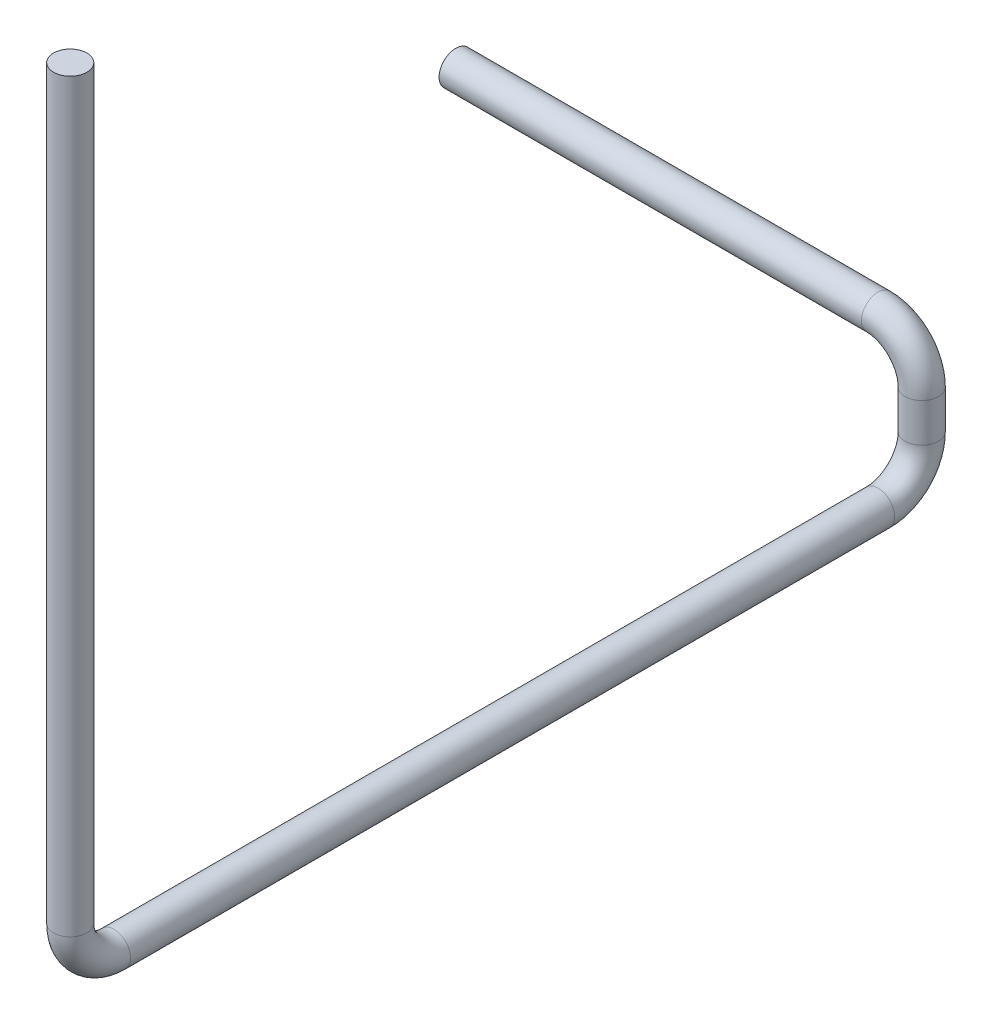
SolidWorks part; units mm, degrees
ref_plane "Alzado" through (0, 0, 0) normal (0, 0, 1) x (1, 0, 0)
ref_plane "Planta" through (0, 0, 0) normal (0, 1, 0) x (1, 0, 0)
ref_plane "Vista lateral" through (0, 0, 0) normal (1, 0, 0) x (0, 0, -1)
sketch3d "Croquis3D2"
  line L1 (1117.59, -243.39, 2257.05) -> (1600.4774, -243.39, 2257.05)
  line L2 (1650.4774, -293.39, 2257.05) -> (1650.4774, -337.5992, 2257.05)
  line L3 (1650.4774, -387.5992, 2307.05) -> (1650.4774, -387.5992, 3180.8059)
  line L4 (1650.4774, -337.5992, 3230.8059) -> (1650.4774, 514.7502, 3230.8059)
  arc A1 (1600.4774, -243.39, 2257.05) -> (1650.4774, -293.39, 2257.05) centre (1600.4774, -293.39, 2257.05) ccw
  arc A2 (1650.4774, -337.5992, 2257.05) -> (1650.4774, -387.5992, 2307.05) centre (1650.4774, -337.5992, 2307.05) ccw
  arc A3 (1650.4774, -387.5992, 3180.8059) -> (1650.4774, -337.5992, 3230.8059) centre (1650.4774, -337.5992, 3180.8059) ccw
  point P3 (1650.4774, -243.39, 2257.05)
  point P6 (1600.4774, -293.39, 2207.05)
  point P22 (1650.4774, -387.5992, 2257.05)
  point P23 (1600.4774, -337.5992, 2307.05)
  point P26 (1650.4774, -387.5992, 3230.8059)
  point P27 (1600.4774, -337.5992, 3180.8059)
  dimension "D1" = 50
  dimension "D2" = 532.8873
  dimension "D3" = 902.3494
  dimension "D4" = 973.7559
  dimension "D5" = 144.2091
sweep "Barrer2" add path "Croquis3D2" circular profile diameter 38.1 parameters "D3"=38.1
